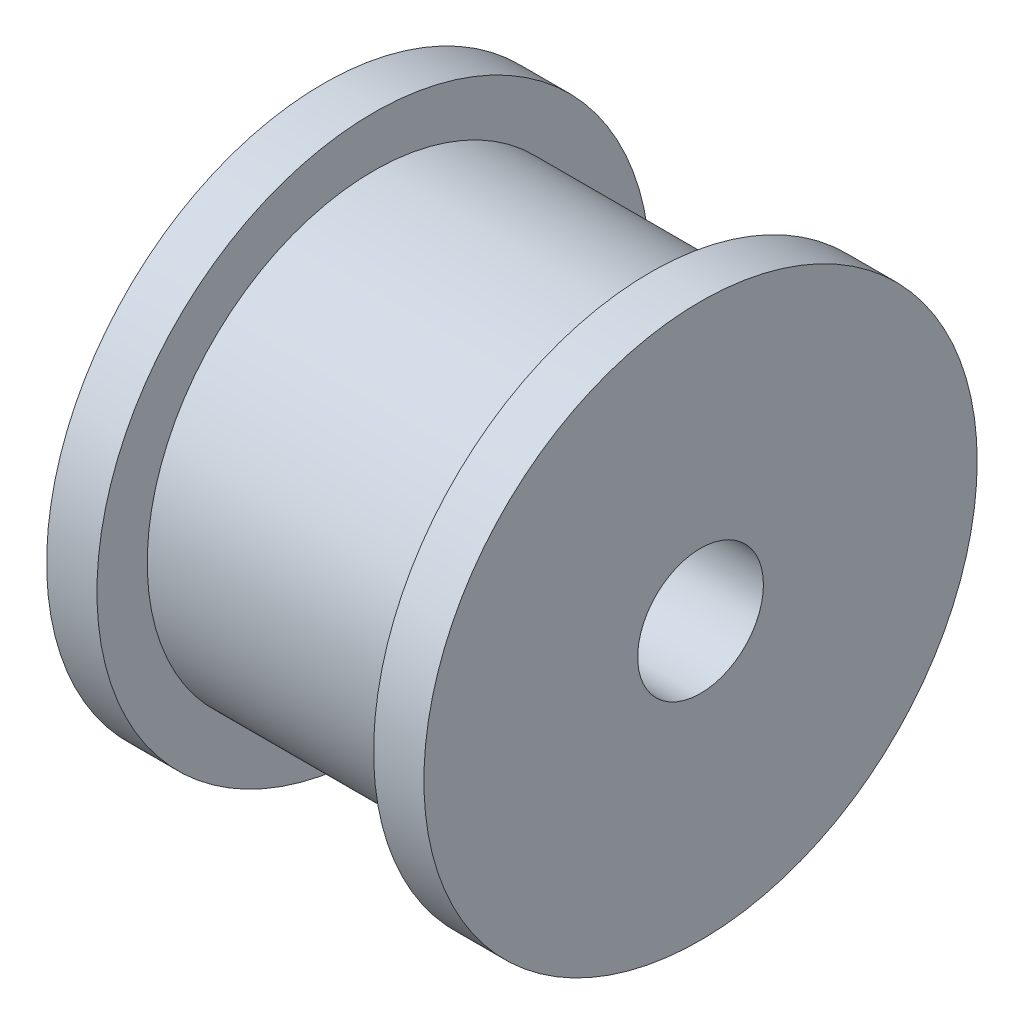
SolidWorks part; units mm, degrees
ref_plane "前视基准面" through (0, 0, 0) normal (0, 0, 1) x (1, 0, 0)
ref_plane "上视基准面" through (0, 0, 0) normal (0, 1, 0) x (1, 0, 0)
ref_plane "右视基准面" through (0, 0, 0) normal (1, 0, 0) x (0, 0, -1)
sketch "草图1" plane through (0, 0, 0) normal (1, 0, 0) x (0, 0, -1)
  circle A0 centre (0, 0) radius 11
  circle A2 centre (0, 0) radius 2.5
extrude "凸台-拉伸1" add sketch "草图1" along normal blind 2
sketch "草图2" plane through (2, 0, 0) normal (1, 0, 0) x (0, 0, -1)
  circle A0 centre (0, 0) radius 9
  circle A1 centre (0, 0) radius 2.5
extrude "凸台-拉伸2" add sketch "草图2" along normal blind 11
sketch "草图3" plane through (13, 0, 0) normal (1, 0, 0) x (0, 0, -1)
  circle A0 centre (0, 0) radius 11
  circle A1 centre (0, 0) radius 2.5
extrude "凸台-拉伸3" add sketch "草图3" along normal blind 2
